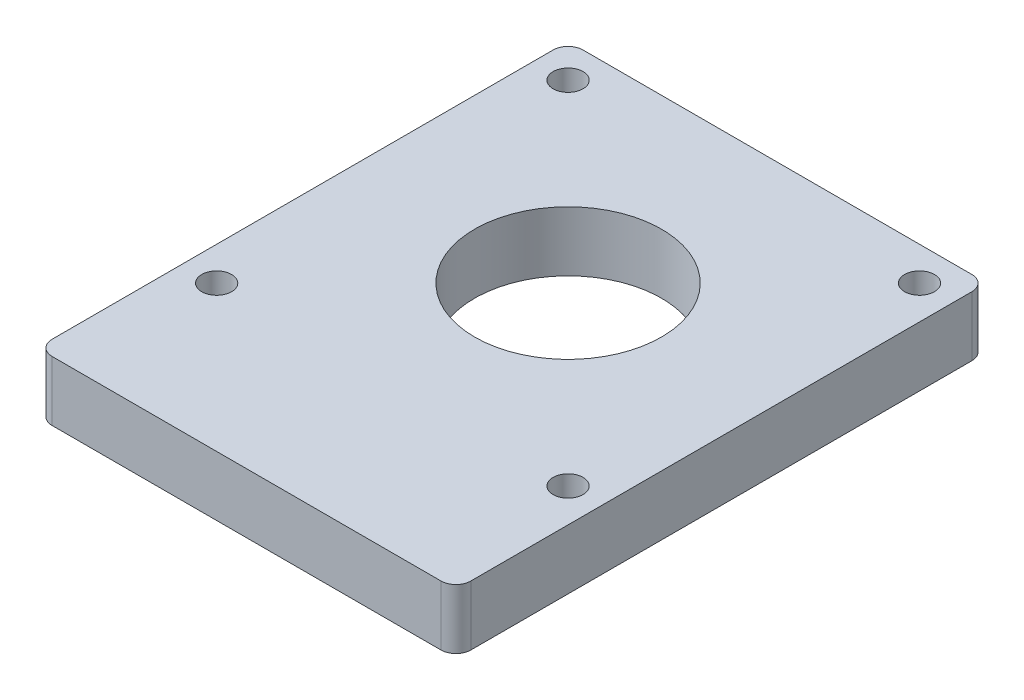
SolidWorks part; units mm, degrees
ref_plane "Front Plane" through (0, 0, 0) normal (0, 0, 1) x (1, 0, 0)
ref_plane "Top Plane" through (0, 0, 0) normal (0, 1, 0) x (1, 0, 0)
ref_plane "Right Plane" through (0, 0, 0) normal (1, 0, 0) x (0, 0, -1)
sketch "Sketch1" plane through (0, 0, 0) normal (0, 1, 0) x (1, 0, 0)
  line L1 (0, 0) -> (56, 0)
  line L2 (0, 0) -> (0, 71)
  line L3 (0, 71) -> (56, 71)
  line L4 (56, 0) -> (56, 71)
  dimension "D1" = 56
  dimension "D2" = 71
extrude "Boss-Extrude1" add sketch "Sketch1" along normal blind 8
fillet "Fillet1" radius 2 4 edges at (0, 4, -71) (56, 4, -71) (56, 4, 0) (0, 4, 0)
sketch "Sketch2" plane through (0, 8, 0) normal (0, 1, 0) x (1, 0, 0)
  line L0 (28, 71) -> (28, 0) construction
  line L1 (54, 71) -> (2, 71) construction
  line L2 (2, 0) -> (54, 0) construction
  line L4 (4.5, 19.5) -> (51.5, 19.5) construction
  line L5 (4.5, 19.5) -> (4.5, 66.5) construction
  line L6 (4.5, 66.5) -> (51.5, 66.5) construction
  line L7 (51.5, 19.5) -> (51.5, 66.5) construction
  line L8 (4.5, 19.5) -> (51.5, 66.5) construction
  line L9 (4.5, 66.5) -> (51.5, 19.5) construction
  circle A0 centre (4.5, 66.5) radius 2
  circle A1 centre (51.5, 66.5) radius 2
  circle A2 centre (51.5, 19.5) radius 2
  circle A3 centre (4.5, 19.5) radius 2
  circle A4 centre (28, 43) radius 12.5
  point P6 (28, 43)
  dimension "D3" = 4
  dimension "D4" = 25
  dimension "D1" = 47
  dimension "D2" = 4.5
extrude "Cut-Extrude1" cut sketch "Sketch2" against normal through all
